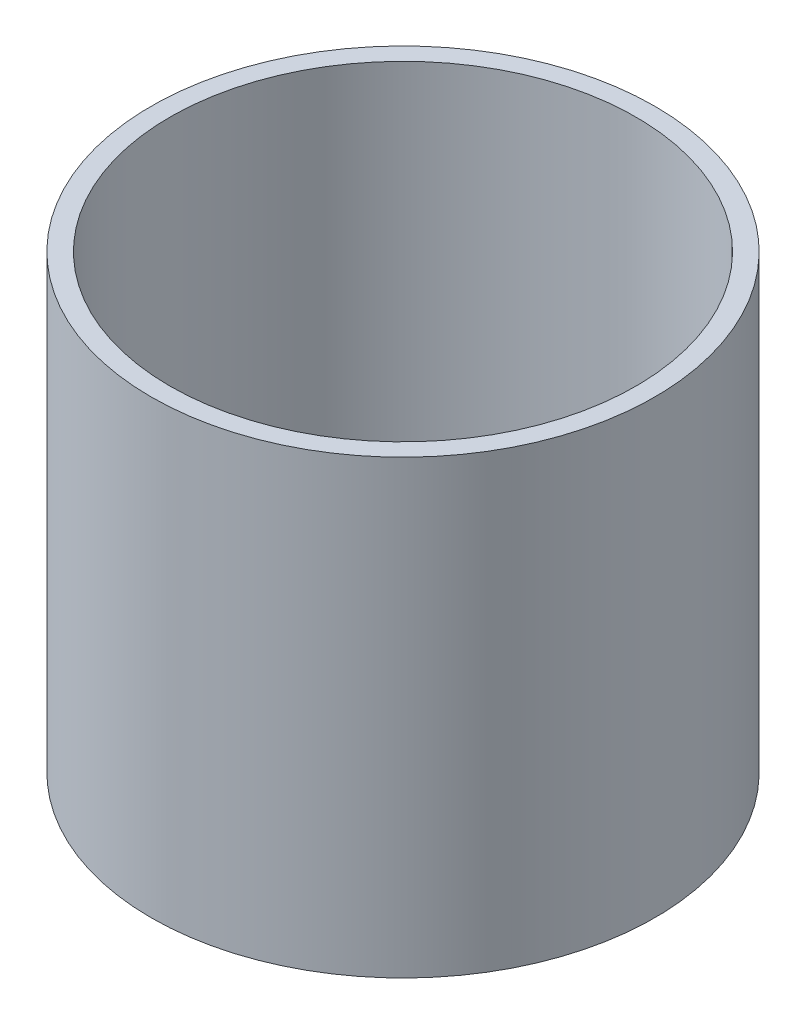
SolidWorks part; units mm, degrees
ref_plane "Front Plane" through (0, 0, 0) normal (0, 0, 1) x (1, 0, 0)
ref_plane "Top Plane" through (0, 0, 0) normal (0, 1, 0) x (1, 0, 0)
ref_plane "Right Plane" through (0, 0, 0) normal (1, 0, 0) x (0, 0, -1)
sketch "Sketch1" plane through (0, 0, 0) normal (0, 1, 0) x (1, 0, 0)
  circle A0 centre (0, 0) radius 33.5
  circle A1 centre (0, 0) radius 31
  dimension "D2" = 67
  dimension "D3" = 62
extrude "Boss-Extrude1" add sketch "Sketch1" along normal blind 60
